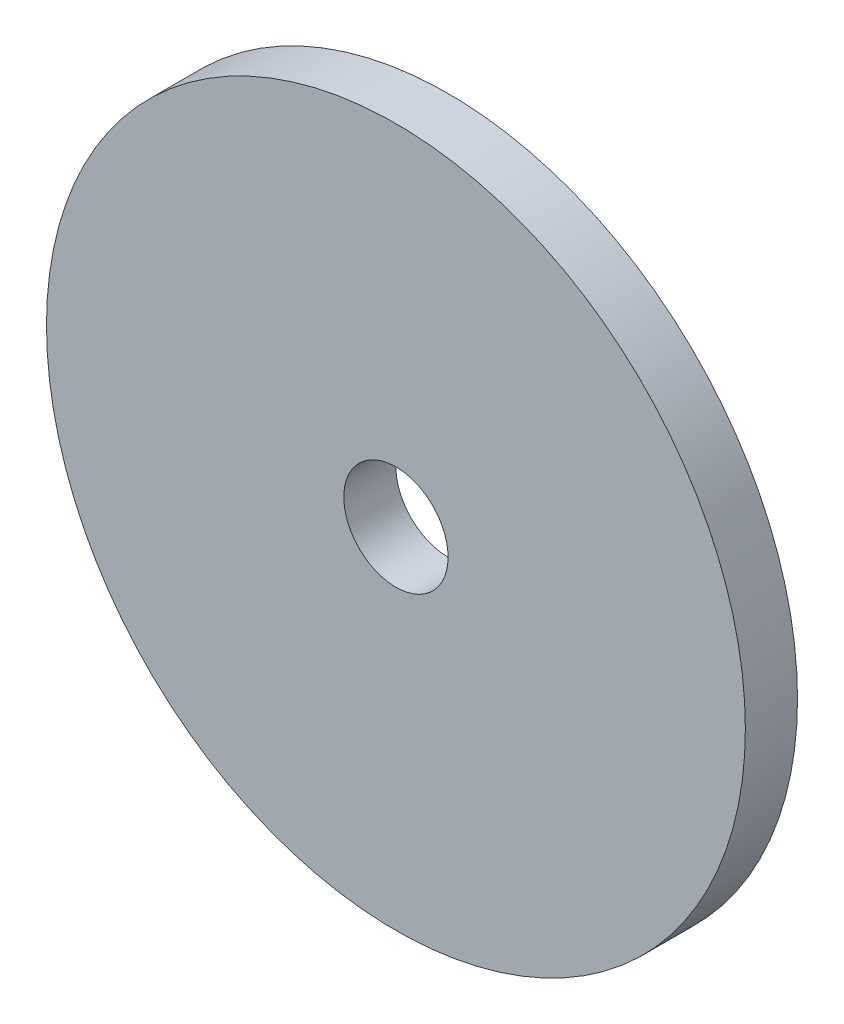
SolidWorks part; units mm, degrees
material "Silicon Rubber"
ref_plane "Front Plane" through (0, 0, 0) normal (0, 0, 1) x (1, 0, 0)
ref_plane "Top Plane" through (0, 0, 0) normal (0, 1, 0) x (1, 0, 0)
ref_plane "Right Plane" through (0, 0, 0) normal (1, 0, 0) x (0, 0, -1)
sketch "Sketch2" plane through (0, 0, 0) normal (0, 0, 1) x (1, 0, 0)
  circle A0 centre (0, 0) radius 33.5
  dimension "D1" = 67
extrude "Boss-Extrude1" add sketch "Sketch2" along normal blind 5
sketch "Sketch3" plane through (0, 0, 5) normal (0, 0, 1) x (1, 0, 0)
  circle A0 centre (0, 0) radius 5
  dimension "D1" = 10
extrude "Cut-Extrude1" cut sketch "Sketch3" against normal through all
